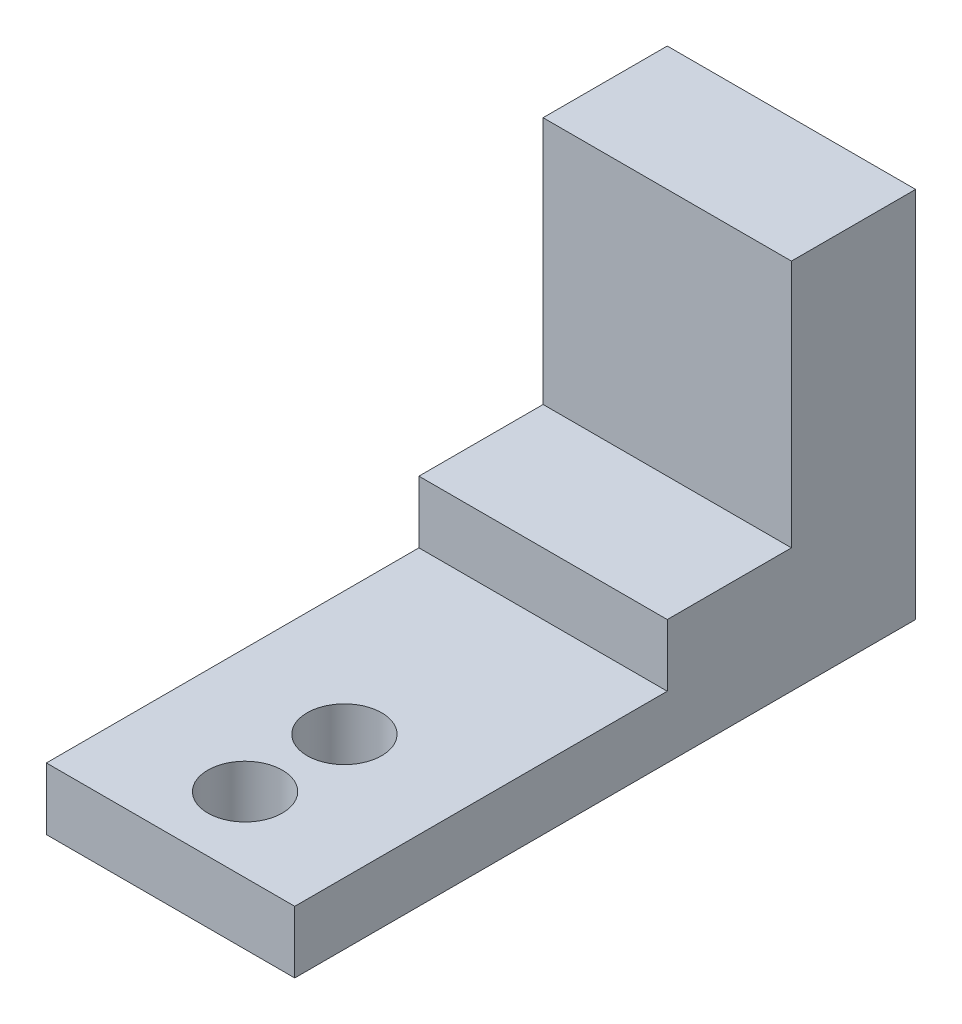
SolidWorks part; units mm, degrees
ref_plane "Front Plane" through (0, 0, 0) normal (0, 0, 1) x (1, 0, 0)
ref_plane "Top Plane" through (0, 0, 0) normal (0, 1, 0) x (1, 0, 0)
ref_plane "Right Plane" through (0, 0, 0) normal (1, 0, 0) x (0, 0, -1)
sketch "Sketch1" plane through (0, 0, 0) normal (0, 0, 1) x (1, 0, 0)
  line L1 (0, 0) -> (10, 0)
  line L2 (0, 0) -> (0, -2.5)
  line L3 (0, -2.5) -> (10, -2.5)
  line L4 (10, 0) -> (10, -2.5)
  dimension "D1" = 10
  dimension "D2" = 2.5
extrude "Boss-Extrude1" add sketch "Sketch1" along normal blind 15
sketch "Sketch2" plane through (0, 0, 0) normal (0, 1, 0) x (1, 0, 0)
  line L0 (10, -15) -> (0, -15) construction
  line L1 (10, 0) -> (0, 0) construction
  circle A0 centre (5, -12) radius 1.5
  circle A1 centre (5, -8) radius 1.5
  dimension "D1" = 3
  dimension "D2" = 8
extrude "Cut-Extrude1" cut sketch "Sketch2" against normal blind 15
sketch "Sketch3" plane through (0, 0, 0) normal (0, 0, -1) x (-1, 0, 0)
  line L1 (-10, -2.5) -> (0, -2.5)
  line L2 (-10, -2.5) -> (-10, 2.5)
  line L3 (-10, 2.5) -> (0, 2.5)
  line L4 (0, -2.5) -> (0, 2.5)
  dimension "D1" = 5
extrude "Boss-Extrude2" add sketch "Sketch3" along normal blind 10
sketch "Sketch4" plane through (0, 2.5, 0) normal (0, 1, 0) x (1, 0, 0)
  line L0 (10, 10) -> (10, 0) construction
  line L1 (0, 10) -> (10, 10)
  line L2 (0, 10) -> (0, 5)
  line L3 (0, 5) -> (10, 5)
  line L4 (10, 10) -> (10, 5)
extrude "Boss-Extrude3" add sketch "Sketch4" along normal blind 10
